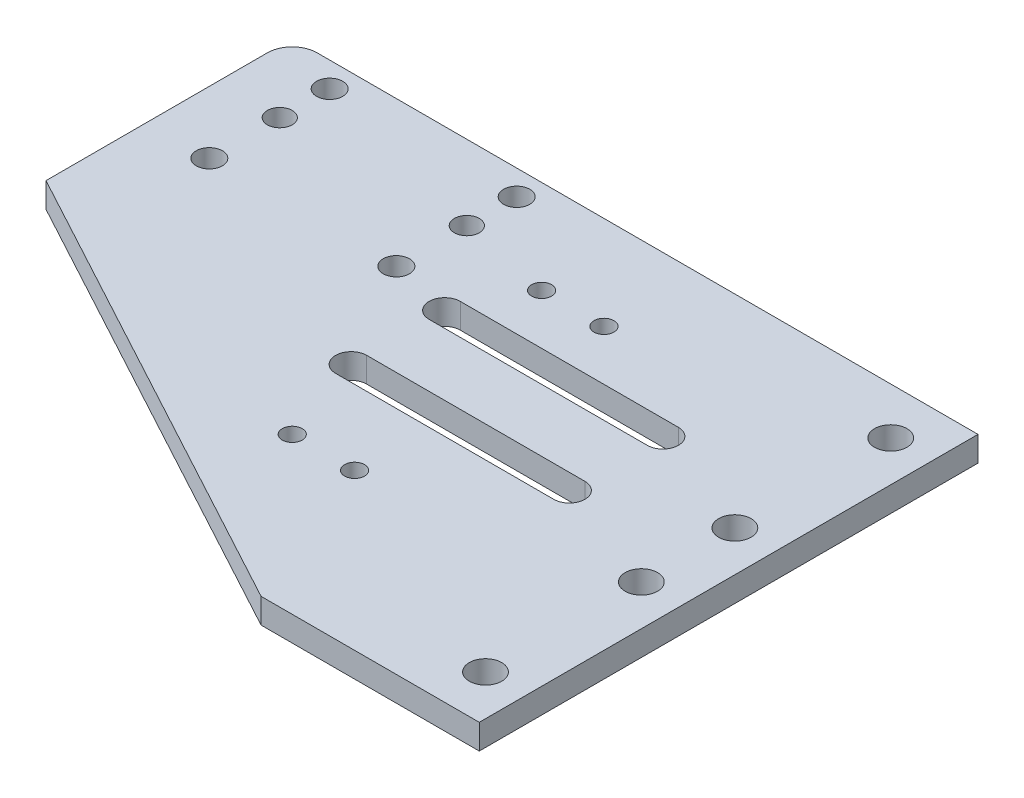
SolidWorks part; units mm, degrees
material "Thornel Mat VMA"
ref_plane "前视基准面" through (0, 0, 0) normal (0, 0, 1) x (1, 0, 0)
ref_plane "上视基准面" through (0, 0, 0) normal (0, 1, 0) x (1, 0, 0)
ref_plane "右视基准面" through (0, 0, 0) normal (1, 0, 0) x (0, 0, -1)
sketch "草图1" plane through (0, 0, 0) normal (0, 1, 0) x (1, 0, 0)
  line L1 (0, 0) -> (110, 0)
  line L2 (0, 0) -> (0, 80)
  line L3 (0, 80) -> (110, 80)
  line L4 (110, 0) -> (110, 80)
  dimension "D1" = 80
  dimension "D2" = 110
extrude "凸台-拉伸1" add sketch "草图1" along normal blind 4
sketch "草图2" plane through (0, 4, 0) normal (0, 1, 0) x (1, 0, 0)
  line L0 (25, -972.0474) -> (25, 49027.9526) construction
  line L1 (0, 80) -> (0, 0) construction
  line L2 (110, 80) -> (0, 80) construction
  circle A0 centre (10, 56.7) radius 2.1
  circle A1 centre (40, 56.7) radius 2.1
  circle A4 centre (10, 76) radius 2.1
  circle A5 centre (40, 76) radius 2.1
  dimension "D2" = 4.2
  dimension "D5" = 4.2
  dimension "D6" = 4
  dimension "D1" = 25
  dimension "D3" = 30
  dimension "D4" = 19.3
extrude "切除-拉伸1" cut sketch "草图2" against normal blind 4
fillet "圆角1" radius 4 1 edges at (0, 2, -80)
fillet "圆角2" radius 5 1 edges at (0, 2, 0)
sketch "草图4" plane through (0, 4, 0) normal (0, 1, 0) x (1, 0, 0)
  line L0 (-894.8059, 40) -> (49105.1941, 40) construction
  line L1 (110, 80) -> (4, 80) construction
  line L2 (5, 0) -> (110, 0) construction
  line L3 (110, 0) -> (110, 80) construction
  circle A0 centre (103.5, 47.5) radius 2.6
  circle A1 centre (103.5, 72.5) radius 2.6
  circle A2 centre (103.5, 7.5) radius 2.6
  circle A3 centre (103.5, 32.5) radius 2.6
  dimension "D1" = 5.2
  dimension "D2" = 25
  dimension "D3" = 15
  dimension "D4" = 6.5
extrude "切除-拉伸2" cut sketch "草图4" against normal blind 10
sketch "草图5" plane through (0, 0, 0) normal (0, -1, 0) x (1, 0, 0)
  line L2 (0, -76) -> (0, -5) construction
  line L3 (110, -80) -> (4, -80) construction
  circle A0 centre (55, -65) radius 1.6
  circle A1 centre (65, -65) radius 1.6
  dimension "D1" = 3.2
  dimension "D2" = 10
  dimension "D4" = 15
  dimension "D3" = 55
extrude "切除-拉伸3" cut sketch "草图5" against normal blind 10
sketch "草图6" plane through (0, 0, 0) normal (0, -1, 0) x (1, 0, 0)
  line L1 (0, -76) -> (0, -5) construction
  line L3 (5, 0) -> (110, 0) construction
  line L4 (0, -40.5) -> (75, 0)
  line L5 (0, -40.5) -> (0, 0)
  line L6 (0, 0) -> (75, 0)
  dimension "D1" = 75
extrude "切除-拉伸4" cut sketch "草图6" against normal blind 10
sketch "草图7" plane through (0, 0, 0) normal (0, -1, 0) x (-1, 0, 0)
  line L0 (-35, 40) -> (-85, 40) construction
  line L1 (-35, 36.8) -> (-85, 36.8)
  line L2 (-35, 43.2) -> (-85, 43.2)
  line L3 (-45, 30) -> (-85, 30) construction
  line L4 (-45, 26.8) -> (-85, 26.8)
  line L5 (-45, 33.2) -> (-85, 33.2)
  line L9 (-110, 0) -> (-110, 80) construction
  arc A0 (-35, 36.8) -> (-35, 43.2) centre (-35, 40) ccw
  arc A1 (-85, 43.2) -> (-85, 36.8) centre (-85, 40) ccw
  arc A2 (-45, 26.8) -> (-45, 33.2) centre (-45, 30) ccw
  arc A3 (-85, 33.2) -> (-85, 26.8) centre (-85, 30) ccw
  point P2 (-60, 40)
  point P7 (-65, 30)
  dimension "D3" = 3.2
  dimension "D4" = 3.2
  dimension "D11" = 25
  dimension "D6" = 10
  dimension "D7" = 40
  dimension "D8" = 50
  dimension "D10" = 25
extrude "切除-拉伸5" [suppressed] cut sketch "草图7" against normal blind 10
sketch "草图8" plane through (0, 0, 0) normal (0, -1, 0) x (1, 0, 0)
  circle A0 centre (10, -68) radius 2
  circle A1 centre (40, -68) radius 2
  circle A3 centre (10, -76) radius 2.1 construction
  dimension "D1" = 4
  dimension "D2" = 4
  dimension "D3" = 8
extrude "切除-拉伸6" cut sketch "草图8" against normal up to next
ref_plane "基准面1" through (0, 0, -45) normal (0, 0, -1) x (-1, 0, 0)
mirror "镜向1" about plane through (0, 0, -45) normal (0, 0, -1) of "切除-拉伸3"
sketch "草图9" plane through (0, 0, 0) normal (0, -1, 0) x (1, 0, 0)
  line L1 (85, -36.9491) -> (50, -36.9491)
  line L3 (85, -41.9491) -> (50, -41.9491)
  line L5 (85, -51.9491) -> (50, -51.9491)
  line L7 (85, -56.9491) -> (50, -56.9491)
  arc A0 (85, -36.9491) -> (85, -41.9491) centre (85, -39.4491) cw
  arc A1 (50, -41.9491) -> (50, -36.9491) centre (50, -39.4491) cw
  arc A2 (85, -56.9491) -> (85, -51.9491) centre (85, -54.4491) ccw
  arc A3 (50, -56.9491) -> (50, -51.9491) centre (50, -54.4491) cw
  dimension "D1" = 5
  dimension "D2" = 5
  dimension "D3" = 35
  dimension "D4" = 35
  dimension "D6" = 10
extrude "切除-拉伸7" cut sketch "草图9" against normal through all
